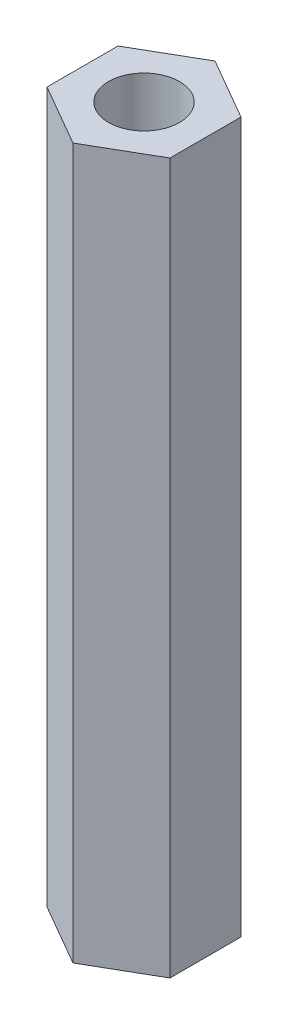
SolidWorks part; units mm, degrees
ref_plane "Спереди" through (0, 0, 0) normal (0, 0, 1) x (1, 0, 0)
ref_plane "Сверху" through (0, 0, 0) normal (0, 1, 0) x (1, 0, 0)
ref_plane "Справа" through (0, 0, 0) normal (1, 0, 0) x (0, 0, -1)
other "Configuration Table"
sketch "Эскиз1" plane through (0, 0, 0) normal (0, 1, 0) x (1, 0, 0)
  line L3 (2.5981, 1.5) -> (0, 3)
  line L4 (-2.5981, 1.5) -> (0, 3)
  line L5 (-2.5981, 1.5) -> (-2.5981, -1.5)
  line L6 (2.5981, 1.5) -> (2.5981, -1.5)
  line L7 (-2.5981, -1.5) -> (0, -3)
  line L8 (0, -3) -> (2.5981, -1.5)
  circle A1 centre (0, 0) radius 3
  circle A6 centre (0, 0) radius 1.5
extrude "Бобышка-Вытянуть1" add sketch "Эскиз1" along normal blind 30 contours L7 L8 L6 L3 L4 L5 A6
